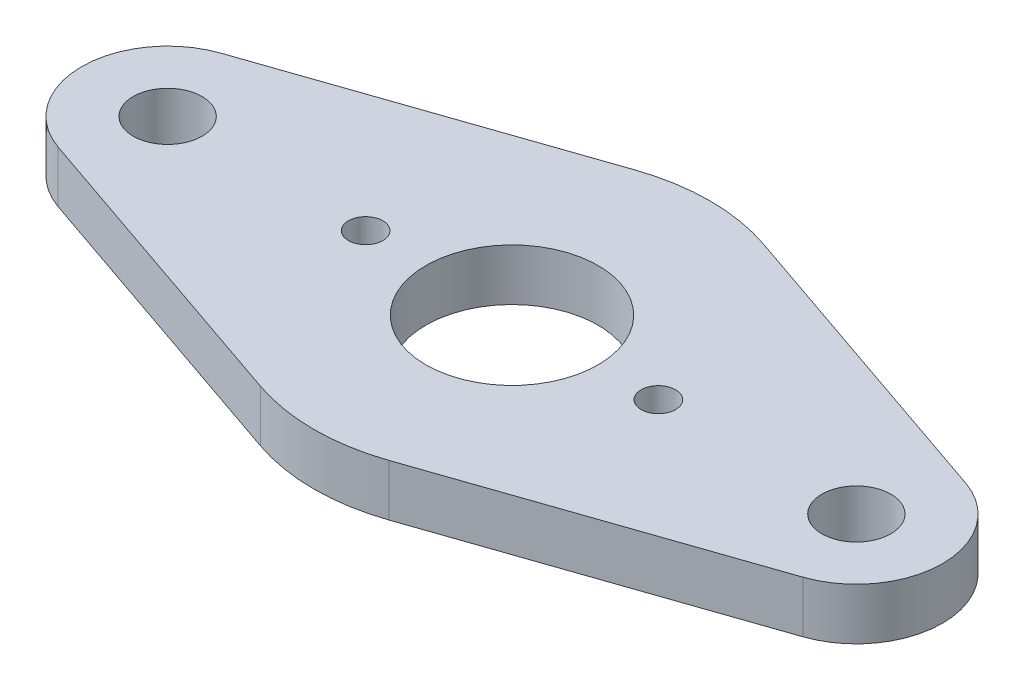
SolidWorks part; units mm, degrees
material "Delrin 2700 NC010, Low Viscosity Acetal Copolymer (SS)"
ref_plane "Front Plane" through (0, 0, 0) normal (0, 0, 1) x (1, 0, 0)
ref_plane "Top Plane" through (0, 0, 0) normal (0, 1, 0) x (1, 0, 0)
ref_plane "Right Plane" through (0, 0, 0) normal (1, 0, 0) x (0, 0, -1)
sketch "Sketch1" plane through (0, 0, 0) normal (0, 1, 0) x (1, 0, 0)
  line L0 (0, 0) -> (0, -27.5855) construction
  line L1 (-8.5, 0) -> (8.5, 0) construction
  line L2 (-21.625, 4.7286) -> (-3.7375, 10.8757)
  line L3 (-21.625, -4.7286) -> (-3.7375, -10.8757)
  line L4 (21.625, -4.7286) -> (3.7375, -10.8757)
  line L5 (21.625, 4.7286) -> (3.7375, 10.8757)
  arc A0 (-3.7375, -10.8757) -> (3.7375, -10.8757) centre (0, 0) ccw
  circle A1 centre (-20, 0) radius 2
  circle A2 centre (-8.5, 0) radius 1
  arc A3 (-21.625, 4.7286) -> (-21.625, -4.7286) centre (-20, 0) ccw
  circle A4 centre (8.5, 0) radius 1
  circle A5 centre (20, 0) radius 2
  arc A6 (21.625, 4.7286) -> (21.625, -4.7286) centre (20, 0) cw
  arc A7 (3.7375, 10.8757) -> (-3.7375, 10.8757) centre (0, 0) ccw
  circle A8 centre (0, 0) radius 5
  dimension "D1" = 17
  dimension "D2" = 23
  dimension "D3" = 2
  dimension "D4" = 4
  dimension "D6" = 10
  dimension "D7" = 10
  dimension "D5" = 40
extrude "Boss-Extrude1" add sketch "Sketch1" along normal blind 3
